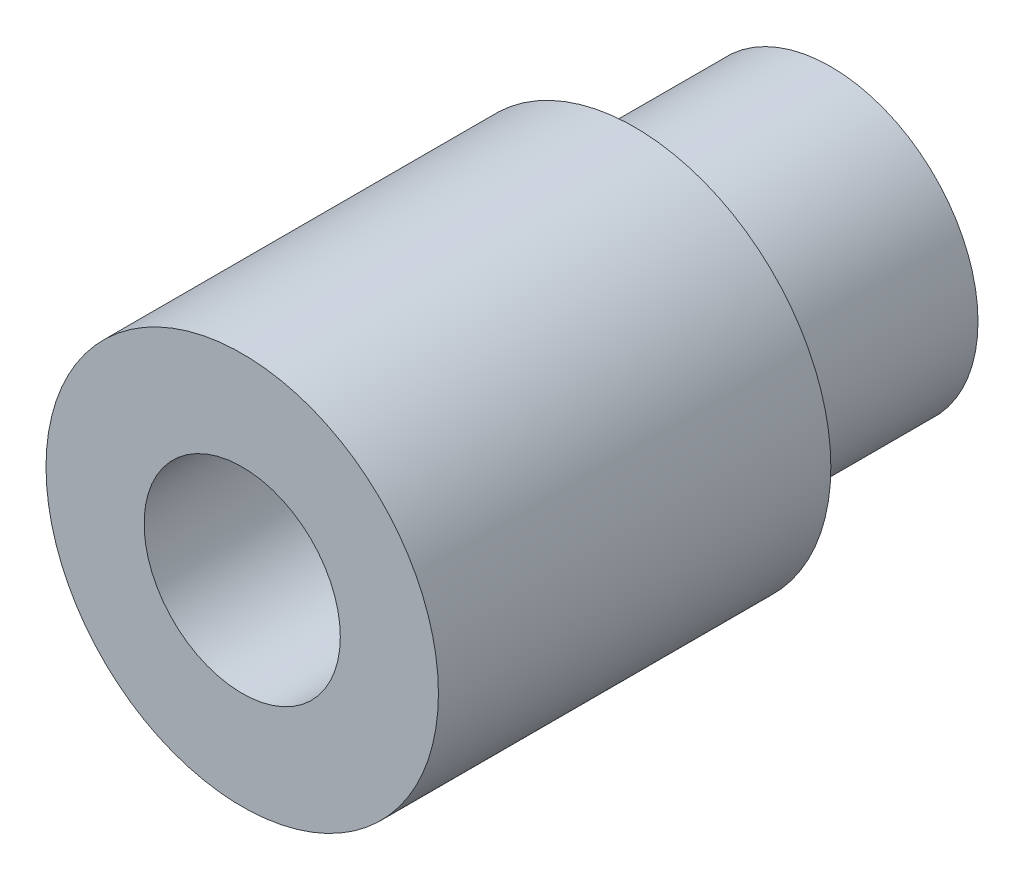
SolidWorks part; units mm, degrees
ref_plane "Спереди" through (0, 0, 0) normal (0, 0, 1) x (1, 0, 0)
ref_plane "Сверху" through (0, 0, 0) normal (0, 1, 0) x (1, 0, 0)
ref_plane "Справа" through (0, 0, 0) normal (1, 0, 0) x (0, 0, -1)
sketch "Эскиз1" plane through (0, 0, 0) normal (0, 0, 1) x (1, 0, 0)
  circle A0 centre (0, 0) radius 3
  dimension "D1" = 6
extrude "Бобышка-Вытянуть1" add sketch "Эскиз1" along normal blind 6
sketch "Эскиз2" plane through (0, 0, 0) normal (0, 0, -1) x (-1, 0, 0)
  circle A0 centre (0, 0.0504) radius 2.25
  dimension "D1" = 4.5
extrude "Бобышка-Вытянуть2" add sketch "Эскиз2" along normal blind 3
sketch "Эскиз3" plane through (0, 0, 6) normal (0, 0, 1) x (1, 0, 0)
  circle A0 centre (0, 0) radius 1.5
  dimension "D1" = 3
extrude "Вырез-Вытянуть1" cut sketch "Эскиз3" against normal blind 10
